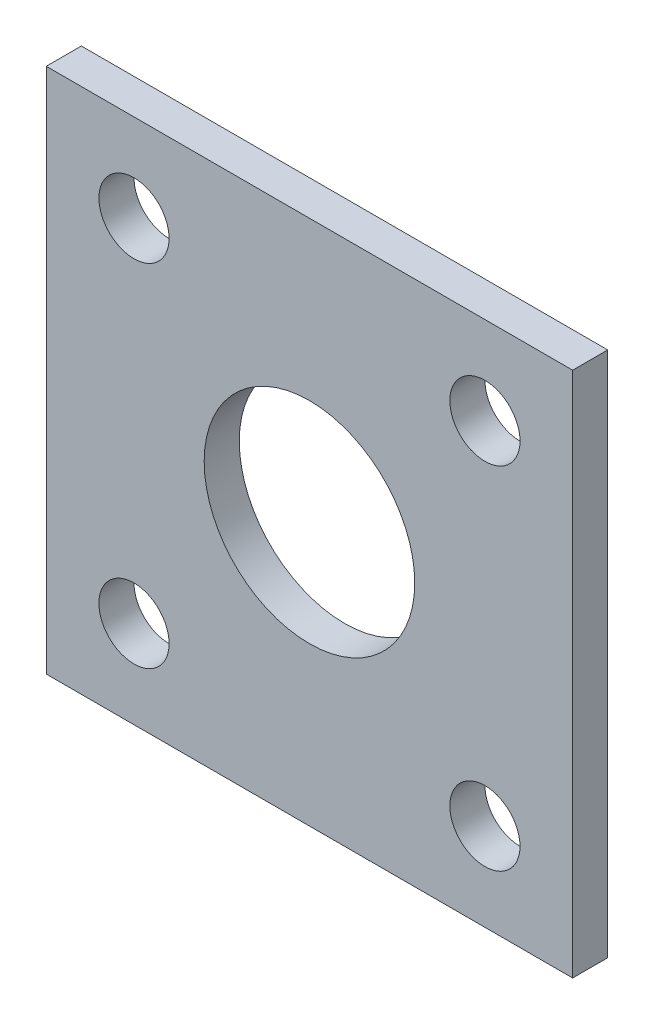
SolidWorks part; units mm, degrees
ref_plane "Front Plane" through (0, 0, 0) normal (0, 0, 1) x (1, 0, 0)
ref_plane "Top Plane" through (0, 0, 0) normal (0, 1, 0) x (1, 0, 0)
ref_plane "Right Plane" through (0, 0, 0) normal (1, 0, 0) x (0, 0, -1)
sketch "Sketch1" plane through (0, 0, 0) normal (0, 0, 1) x (1, 0, 0)
  line L1 (-750, 750) -> (750, 750)
  line L2 (-750, 750) -> (-750, -750)
  line L3 (-750, -750) -> (750, -750)
  line L4 (750, 750) -> (750, -750)
  line L5 (-750, 750) -> (750, -750) construction
  line L6 (-750, -750) -> (750, 750) construction
  line L7 (500, -500) -> (-500, -500) construction
  line L8 (500, -500) -> (500, 500) construction
  line L9 (500, 500) -> (-500, 500) construction
  line L10 (-500, -500) -> (-500, 500) construction
  line L11 (500, -500) -> (-500, 500) construction
  line L12 (500, 500) -> (-500, -500) construction
  circle A0 centre (0, 0) radius 300
  circle A1 centre (-500, 500) radius 100
  circle A2 centre (500, 500) radius 100
  circle A3 centre (500, -500) radius 100
  circle A4 centre (-500, -500) radius 100
  dimension "D3" = 600
  dimension "D5" = 200
  dimension "D1" = 1500
  dimension "D2" = 1500
  dimension "D4" = 1000
extrude "Boss-Extrude1" add sketch "Sketch1" along normal blind 100
